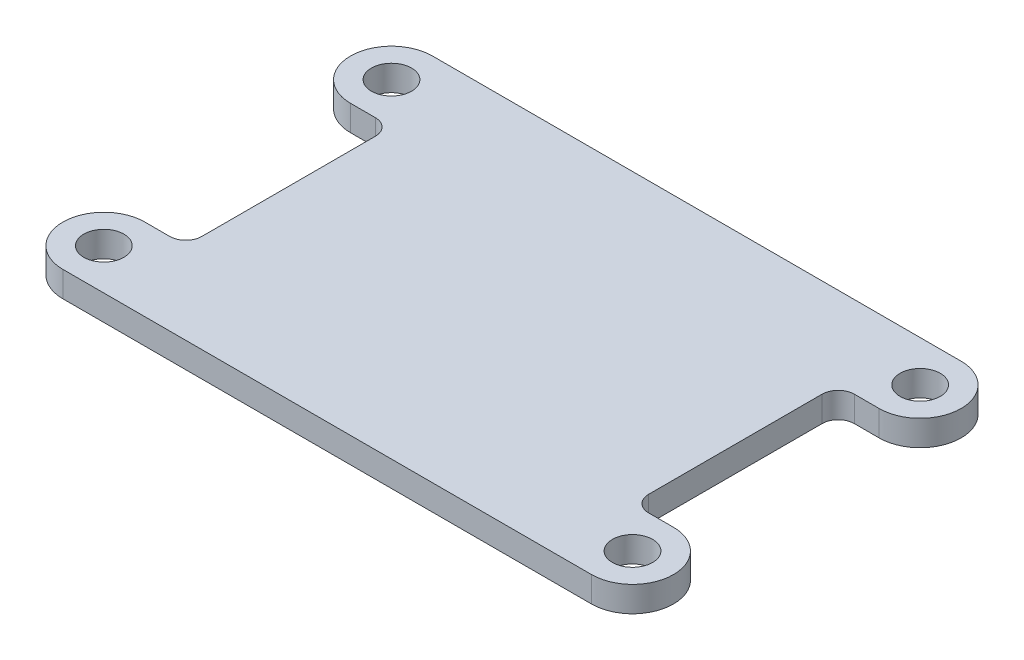
SolidWorks part; units mm, degrees
ref_plane "Front Plane" through (0, 0, 0) normal (0, 0, 1) x (1, 0, 0)
ref_plane "Top Plane" through (0, 0, 0) normal (0, 1, 0) x (1, 0, 0)
ref_plane "Right Plane" through (0, 0, 0) normal (1, 0, 0) x (0, 0, -1)
sketch "Sketch1" plane through (0, 0, 0) normal (0, 1, 0) x (1, 0, 0)
  line L1 (-19, -11.5) -> (19, -11.5)
  line L2 (-19, -11.5) -> (-19, 11.5)
  line L3 (-19, 11.5) -> (19, 11.5)
  line L4 (19, -11.5) -> (19, 11.5)
  line L5 (-19, -11.5) -> (19, 11.5) construction
  line L6 (-19, 11.5) -> (19, -11.5) construction
  point P0 (0, 0)
  dimension "D1" = 38
  dimension "D2" = 23
extrude "Boss-Extrude1" add sketch "Sketch1" along normal blind 1.5875
sketch "Sketch2" plane through (0, 1.5875, 0) normal (0, 1, 0) x (1, 0, 0)
  line L0 (-16.45, 6.4) -> (-14.9, 6.4)
  line L1 (-16.45, 11.5) -> (19, 11.5)
  line L2 (-19, 8.95) -> (-19, -11.5)
  line L3 (-19, -11.5) -> (19, -11.5)
  line L4 (19, 11.5) -> (19, -11.5)
  line L5 (-13.9, 5.4) -> (-13.9, -5.4)
  line L6 (-14.9, -6.4) -> (-16.45, -6.4)
  line L7 (-16.45, -8.95) -> (-16.45, -7.9421) construction
  line L8 (0, 0) -> (0, 7.9601) construction
  line L9 (16.45, -8.95) -> (16.45, -7.9421) construction
  line L10 (14.9, -6.4) -> (16.45, -6.4)
  line L11 (13.9, 5.4) -> (13.9, -5.4)
  line L12 (16.45, 6.4) -> (14.9, 6.4)
  arc A0 (-16.45, 11.5) -> (-19, 8.95) centre (-16.45, 8.95) ccw
  circle A1 centre (-16.45, 8.95) radius 2.55
  circle A2 centre (-16.45, -8.95) radius 2.55
  arc A3 (-14.9, 6.4) -> (-13.9, 5.4) centre (-14.9, 5.4) cw
  arc A4 (-13.9, -5.4) -> (-14.9, -6.4) centre (-14.9, -5.4) cw
  circle A5 centre (-16.45, 8.95) radius 1.25
  circle A6 centre (-16.45, -8.95) radius 1.25
  circle A7 centre (16.45, -8.95) radius 1.25
  circle A8 centre (16.45, 8.95) radius 1.25
  arc A9 (13.9, -5.4) -> (14.9, -6.4) centre (14.9, -5.4) ccw
  arc A10 (14.9, 6.4) -> (13.9, 5.4) centre (14.9, 5.4) ccw
  circle A11 centre (16.45, -8.95) radius 2.55
  circle A12 centre (16.45, 8.95) radius 2.55
  arc A13 (16.45, 11.5) -> (19, 8.95) centre (16.45, 8.95) cw
  point P8 (-19, 11.5)
  point P26 (-16.45, -8.3522)
  point P27 (-16.45, -7.9421)
  line M5 (19, -11.5) -> (19, 11.5)
  line M6 (19, 11.5) -> (-19, 11.5)
  line M7 (-19, 11.5) -> (-19, -11.5)
  line M8 (-19, -11.5) -> (19, -11.5)
  dimension "D1" = 2.55
  dimension "D2" = 1
  dimension "D3" = 2.5
  dimension "D4" = 2.5
extrude "Cut-Extrude1" cut sketch "Sketch2" against normal up to next contours A0 M6 M7 | A5 | A4 L5 A3 L0 A1 A2 L6 M7 | A2 L2 M8 | A6 | A7 | A11 M5 M8 | L4 A12 L12 A10 L11 A9 L10 A11 | A12 M6 M5 | A8
